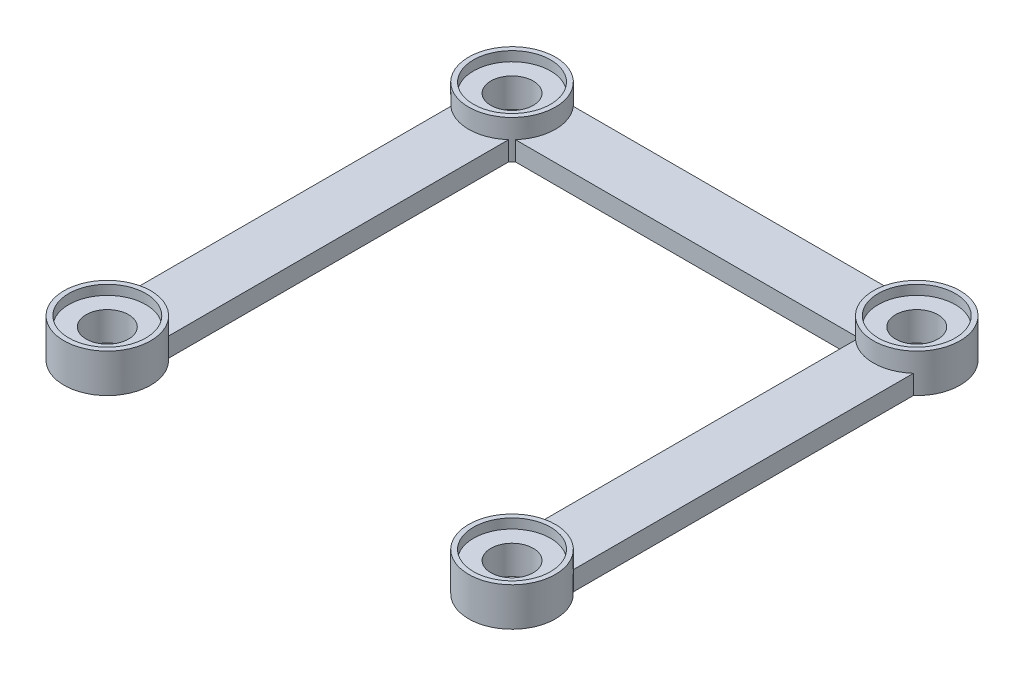
SolidWorks part; units mm, degrees
material "ABS"
ref_plane "Front" through (0, 0, 0) normal (0, 0, 1) x (1, 0, 0)
ref_plane "Top" through (0, 0, 0) normal (0, 1, 0) x (1, 0, 0)
ref_plane "Right" through (0, 0, 0) normal (1, 0, 0) x (0, 0, -1)
sketch "ｽｹｯﾁ1" plane through (0, 0, 0) normal (0, 1, 0) x (1, 0, 0)
  line L1 (-10.5, 1.5) -> (10.5, 1.5)
  line L2 (-10.5, 1.5) -> (-10.5, -1.5)
  line L3 (-10.5, -1.5) -> (10.5, -1.5)
  line L4 (10.5, 1.5) -> (10.5, -1.5)
  line L5 (-10.5, 1.5) -> (10.5, -1.5) construction
  line L6 (-10.5, -1.5) -> (10.5, 1.5) construction
  point P0 (0, 0)
  dimension "D1" = 3
  dimension "D2" = 21
extrude "ﾎﾞｽ - 押し出し1" add sketch "ｽｹｯﾁ1" along normal blind 1
sketch "ｽｹｯﾁ3" plane through (0, 0, 0) normal (0, -1, 0) x (1, 0, 0)
  line L0 (-10.5, -1.5) -> (-10.5, 1.5) construction
  line L1 (-9, 21) -> (-12, 21)
  line L2 (-9, 21) -> (-9, 0)
  line L3 (-9, 0) -> (-12, 0)
  line L4 (-12, 21) -> (-12, 0)
  line L5 (-9, 21) -> (-12, 0) construction
  line L6 (-9, 0) -> (-12, 21) construction
  point P4 (-10.5, 10.5)
  point P6 (-10.5, 0)
  point P9 (-10.5, 0)
  dimension "D3" = 0
  dimension "D1" = 21
  dimension "D2" = 0
  dimension "D4" = 3
extrude "ﾎﾞｽ - 押し出し3" add sketch "ｽｹｯﾁ3" against normal blind 1
sketch "ｽｹｯﾁ2" plane through (0, 0, 0) normal (0, -1, 0) x (1, 0, 0)
  line L1 (-10.5, 0) -> (-10.5, 21) construction
  circle A0 centre (-10.5, 0) radius 2.25
  circle A1 centre (-10.5, 21) radius 2.25
  dimension "D1" = 4.5
  dimension "D2" = 21
extrude "ﾎﾞｽ - 押し出し4" add sketch "ｽｹｯﾁ2" against normal blind 2
hole_wizard "M2 なべ頭ねじ用座ぐり穴2" positions "ｽｹｯﾁ6" profile "ｽｹｯﾁ7" counterbore size "M2" standard "ISO" end condition through all
sketch "ｽｹｯﾁ6" plane through (0, 2, 0) normal (0, 1, 0) x (1, 0, 0)
  point P0 (-10.5, 0)
  point P3 (-10.5, -21)
sketch "ｽｹｯﾁ7" plane through (-10.5, 2, 0) normal (1, 0, 0) x (0, 0, 1)
  line L0 (0, 0) -> (0, 2)
  line L1 (0, 2) -> (1.1, 2)
  line L3 (1.1, 2) -> (1.1, 0.5)
  line L4 (1.1, 0.5) -> (2, 0.5)
  line L5 (2, 0.5) -> (2, 0)
  line L7 (2, 0) -> (0, 0)
  line L11 (0, -6.35) -> (0, 107.95) construction
  dimension "通し穴の直径" = 2.2
  dimension "通し穴の深さ" = 2
  dimension "座ぐり穴の直径" = 4
  dimension "座ぐり穴の深さ" = 0.5
mirror "ﾐﾗｰ2" about plane through (0, 0, 0) normal (1, 0, 0) of "ﾎﾞｽ - 押し出し4", "M2 なべ頭ねじ用座ぐり穴2", "ﾎﾞｽ - 押し出し3"
